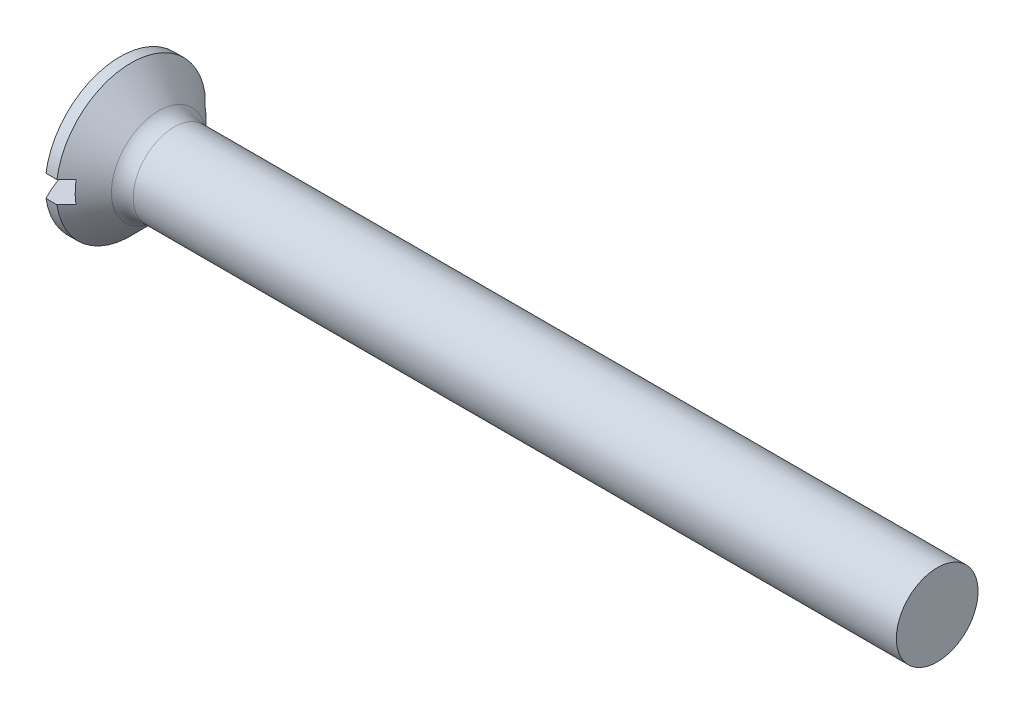
SolidWorks part; units mm, degrees
ref_plane "Plane1" through (0, 0, 0) normal (0, 0, 1) x (1, 0, 0)
ref_plane "Plane2" through (0, 0, 0) normal (0, 1, 0) x (1, 0, 0)
ref_plane "Plane3" through (0, 0, 0) normal (1, 0, 0) x (0, 0, -1)
sketch "BodySke" plane through (0, 0, 0) normal (0, 0, 1) x (1, 0, 0)
  line L0 (0, 0) -> (30.7, 0)
  line L1 (30.7, 0) -> (30.7, 1.5)
  line L2 (30.7, 1.5) -> (2.35, 1.5)
  line L3 (1.1, -2.75) -> (2.35, -1.5) construction
  line L4 (-15.875, 0) -> (82.55, 0) construction
  line L5 (1.1, 2.75) -> (2.35, 1.5)
  line L6 (2.85, 4.675) -> (2.85, -11.2) construction
  line L7 (0.7, 2.7793) -> (0.7, -13.0957) construction
  line L8 (1.1, 2.75) -> (0.7, 2.75)
  arc A0 (0, 0) -> (0.7, 2.75) centre (5.7518, 0) cw
  dimension "Head_ang" = 90
  dimension "Diameter" = 3
  dimension "Advance" = 0.5
  dimension "Thread_nom" = 30
  dimension "Oval_ht" = 0.7
  dimension "Side_ht" = 1.65
  dimension "Head_dia" = 5.5
  dimension "Length" = 30
revolve "Base-Revolve" add sketch "BodySke"
cosmetic thread "ThreadCosmetic" [suppressed]
extrude "Slot" cut sketch "Sketch2" along normal blind 1.45
sketch "Sketch2" plane through (0, 0, 0) normal (1, 0, 0) x (0, 0, -1)
  line L0 (2.75, -0.4) -> (-2.75, -0.4)
  line L1 (2.75, -0.4) -> (2.75, 0.4)
  line L2 (-2.75, 0.4) -> (2.75, 0.4)
  line L3 (-2.75, 0.4) -> (-2.75, -0.4)
  dimension "D1" = 5.5
  dimension "Slot_width" = 0.8
  dimension "D3" = 2.75
  dimension "D4" = 0.4
fillet "Fillet1" radius 0.8 1 edges at (2.35, 0, 1.5)
sketch "ThdSchSke" plane through (0, 0, 0) normal (0, 0, 1) x (1, 0, 0)
  line L0 (2.85, -1.2195) -> (2.6536, -1.5)
  line L1 (2.85, -1.2195) -> (3.0464, -1.5)
  line L2 (3.0464, -1.5) -> (3.0464, -1.875)
  line L3 (-3.175, 0) -> (5.1513, 0) construction
  line L5 (3.0464, -1.875) -> (2.6536, -1.875)
  line L6 (2.6536, -1.875) -> (2.6536, -1.5)
  dimension "Diameter" = 3
  dimension "SideAngle" = 55
  dimension "VeeAngle" = 70
  dimension "Thread_minor" = 2.439
  dimension "Overcut" = 3.75
  dimension "Start" = 2.85
revolve "ThreadSchematic" [suppressed] cut sketch "ThdSchSke" angle 360 about L3
pattern_linear "ThdSchPat" [suppressed]
equation "\"D1@Sketch2\" = \"Head_dia@BodySke\""
equation "\"D3@Sketch2\" = \"D1@Sketch2\" / 2"
equation "\"D4@Sketch2\" = \"Slot_width@Sketch2\" / 2"
equation "\"Thread_length@ThreadCosmetic\" = ((sgn( (\"Length@BodySke\" - \"Advance@BodySke\" - \"Side_ht@BodySke\" ) - \"Thread_nom@BodySke\" )-1)*( (\"Length@BodySke\" - \"Advance@BodySke\" - \"Side_ht@BodySke\" ) - \"Thread_nom@BodySke\" ))/-2+ \"Thread_nom@BodySke\""
equation "\"Thread_minor@ThdSchSke\" = \"Thread_minor@ThreadCosmetic\""
equation "\"Diameter@ThdSchSke\" = \"Diameter@BodySke\""
equation "\"Overcut@ThdSchSke\" = \"Diameter@BodySke\" * 1.25"
equation "\"Start@ThdSchSke\" = \"Oval_ht@BodySke\" + \"Length@BodySke\" - \"Thread_length@ThreadCosmetic\"  '---Countersunk---"
equation "\"Num_threads@ThdSchPat\" = int( \"Thread_length@ThreadCosmetic\" / \"Advance@BodySke\" + 0.999 )  + 1"
equation "\"Advance@ThdSchPat\" = \"Thread_length@ThreadCosmetic\" /  (\"Num_threads@ThdSchPat\" - 1) 'relax it"
